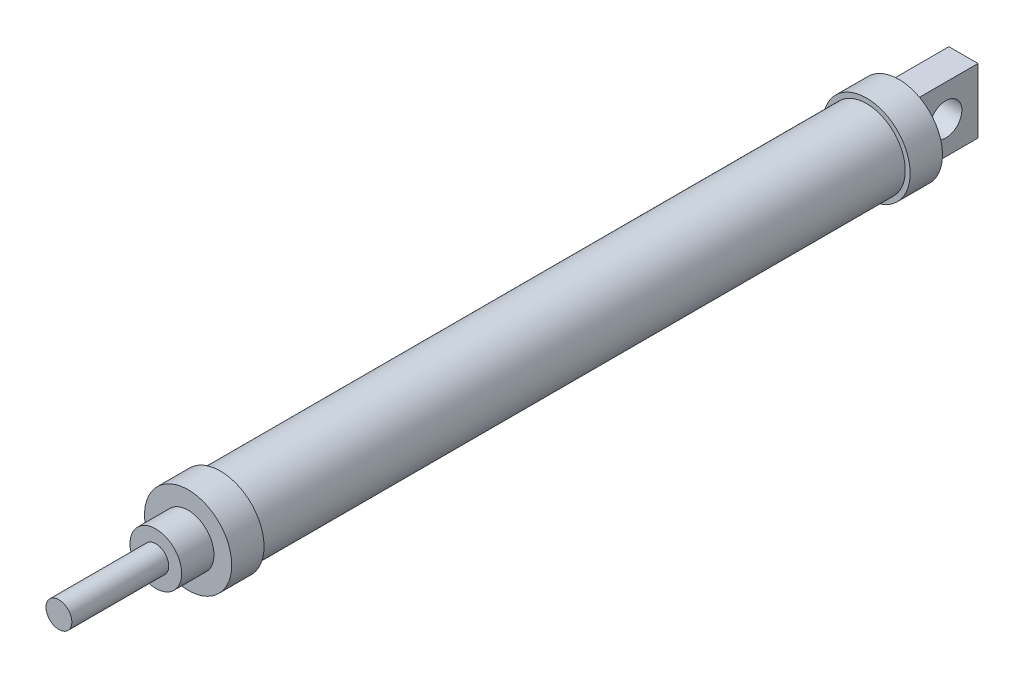
SolidWorks part; units mm, degrees
ref_plane "Front Plane" through (0, 0, 0) normal (0, 0, 1) x (1, 0, 0)
ref_plane "Top Plane" through (0, 0, 0) normal (0, 1, 0) x (1, 0, 0)
ref_plane "Right Plane" through (0, 0, 0) normal (1, 0, 0) x (0, 0, -1)
sketch "Sketch1" plane through (0, 0, 0) normal (0, 0, 1) x (1, 0, 0)
  circle A0 centre (0, 0) radius 13.5
  dimension "D1" = 27
extrude "Boss-Extrude1" add sketch "Sketch1" along normal blind 10
sketch "Sketch2" plane through (0, 0, 10) normal (0, 0, 1) x (1, 0, 0)
  circle A0 centre (0, 0) radius 8
  dimension "D1" = 16
extrude "Boss-Extrude2" add sketch "Sketch2" along normal blind 10
sketch "Sketch3" plane through (0, 0, 0) normal (0, 0, -1) x (-1, 0, 0)
  circle A0 centre (0, 0) radius 12
  dimension "D1" = 24
extrude "Boss-Extrude3" add sketch "Sketch3" along normal blind 200
sketch "Sketch4" plane through (0, 0, -200) normal (0, 0, -1) x (-1, 0, 0)
  circle A0 centre (0, 0) radius 13.5
  dimension "D1" = 27
extrude "Boss-Extrude4" add sketch "Sketch4" along normal blind 10 contours A0
sketch "Sketch5" plane through (0, 0, -210) normal (0, 0, -1) x (-1, 0, 0)
  line L1 (4.5, -10) -> (-4.5, -10)
  line L2 (4.5, -10) -> (4.5, 10)
  line L3 (4.5, 10) -> (-4.5, 10)
  line L4 (-4.5, -10) -> (-4.5, 10)
  line L5 (4.5, -10) -> (-4.5, 10) construction
  line L6 (4.5, 10) -> (-4.5, -10) construction
  point P0 (0, 0)
  dimension "D1" = 9
  dimension "D2" = 20
extrude "Boss-Extrude5" add sketch "Sketch5" along normal blind 20
sketch "Sketch6" plane through (4.5, 0, 0) normal (1, 0, 0) x (0, 0, -1)
  line L0 (210, 10) -> (230, -10) construction
  line L1 (230, -10) -> (210, -10) construction
  line L2 (230, -10) -> (230, 10) construction
  line L3 (230, 10) -> (210, -10) construction
  circle A0 centre (220, 0) radius 5
  dimension "D1" = 10
extrude "Cut-Extrude1" cut sketch "Sketch6" against normal blind 20 contours A0
sketch "Sketch8" plane through (0, 0, 20) normal (0, 0, 1) x (1, 0, 0)
  circle A0 centre (0, 0) radius 4
  dimension "D1" = 8
extrude "Boss-Extrude6" add sketch "Sketch8" along normal blind 30
